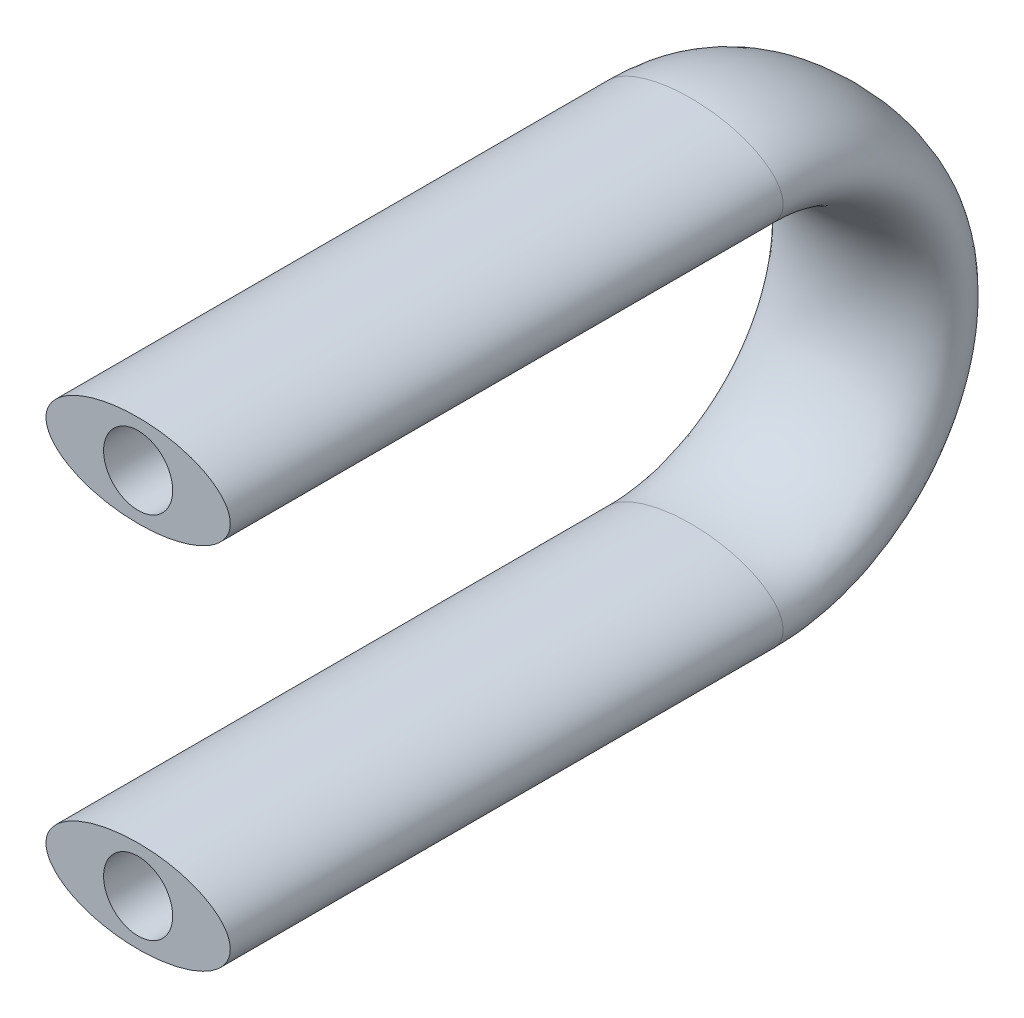
SolidWorks part; units mm, degrees
ref_plane "Front Plane" through (0, 0, 0) normal (0, 0, 1) x (1, 0, 0)
ref_plane "Top Plane" through (0, 0, 0) normal (0, 1, 0) x (1, 0, 0)
ref_plane "Right Plane" through (0, 0, 0) normal (1, 0, 0) x (0, 0, -1)
sketch "Sketch1" plane through (0, 0, 0) normal (1, 0, 0) x (0, 0, -1)
  line L0 (0, 0) -> (304.8, 0)
  line L1 (0, 203.2) -> (304.8, 203.2)
  arc A0 (304.8, 203.2) -> (304.8, 0) centre (304.8, 101.6) cw
  dimension "D1" = 101.6
  dimension "D2" = 304.8
  dimension "D3" = 304.8
  dimension "D4" = 203.2
sketch "Sketch4" plane through (0, 0, 0) normal (0, 0, 1) x (1, 0, 0)
  circle A0 centre (0, 0) radius 19.05
  ellipse E0 centre (0, 0) end of major axis (-50.8, 0) minor radius 25.4
  dimension "D1" = 38.1
  dimension "D2" = 101.6
  dimension "D3" = 50.8
sweep "Sweep2" add profiles "Sketch4" path "Sketch1"
